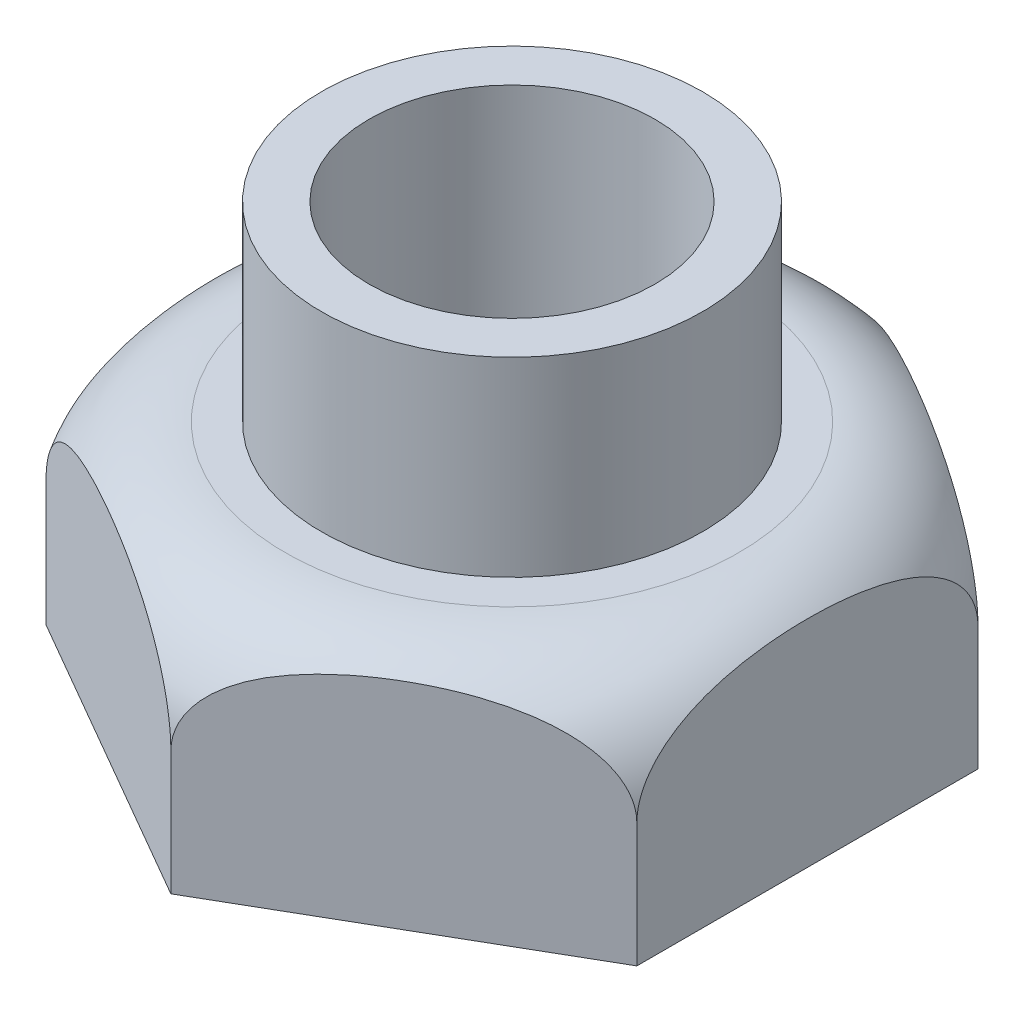
SolidWorks part; units mm, degrees
ref_plane "Front Plane" through (0, 0, 0) normal (0, 0, 1) x (1, 0, 0)
ref_plane "Top Plane" through (0, 0, 0) normal (0, 1, 0) x (1, 0, 0)
ref_plane "Right Plane" through (0, 0, 0) normal (1, 0, 0) x (0, 0, -1)
sketch "Sketch1" plane through (0, 0, 0) normal (0, 1, 0) x (1, 0, 0)
  line L1 (19.685, -11.3651) -> (19.685, 11.3651)
  line L2 (19.685, 11.3651) -> (0, 22.7303)
  line L3 (0, 22.7303) -> (-19.685, 11.3651)
  line L4 (-19.685, 11.3651) -> (-19.685, -11.3651)
  line L5 (-19.685, -11.3651) -> (0, -22.7303)
  line L6 (0, -22.7303) -> (19.685, -11.3651)
  circle A0 centre (0, 0) radius 19.685 construction
  dimension "D1" = 39.37
extrude "Boss-Extrude1" add sketch "Sketch1" along normal blind 15.875
sketch "Sketch2" plane through (0, 0, 0) normal (1, 0, 0) x (0, 0, -1)
  line L0 (0, 0) -> (0, 8.679) construction
  line L1 (22.7303, 0) -> (28.4756, 0)
  line L2 (11.3651, 15.875) -> (22.7303, 15.875) construction
  line L3 (11.3651, 15.875) -> (15.1103, 15.875)
  line L4 (22.7303, 15.875) -> (22.7303, 0) construction
  line L5 (22.7303, 8.255) -> (22.7303, 0)
  line L6 (11.3651, 15.875) -> (11.3651, 20.4738)
  line L7 (11.3651, 20.4738) -> (28.4756, 20.4738)
  line L8 (28.4756, 20.4738) -> (28.4756, 0)
  arc A0 (15.1103, 15.875) -> (22.7303, 8.255) centre (15.1103, 8.255) cw
  point P4 (0, 0)
  dimension "D1" = 7.62
revolve "Cut-Revolve1" cut sketch "Sketch2" angle 360 about L0
sketch "Sketch3" plane through (0, 15.875, 0) normal (0, 1, 0) x (1, 0, 0)
  circle A1 centre (0, 0) radius 12.7
  dimension "D1" = 25.4
extrude "Boss-Extrude2" add sketch "Sketch3" along normal blind 12.7
sketch "Sketch4" plane through (0, 28.575, 0) normal (0, 1, 0) x (1, 0, 0)
  circle A0 centre (0, 0) radius 9.525
  dimension "D1" = 19.05
extrude "Cut-Extrude1" cut sketch "Sketch4" against normal through all
